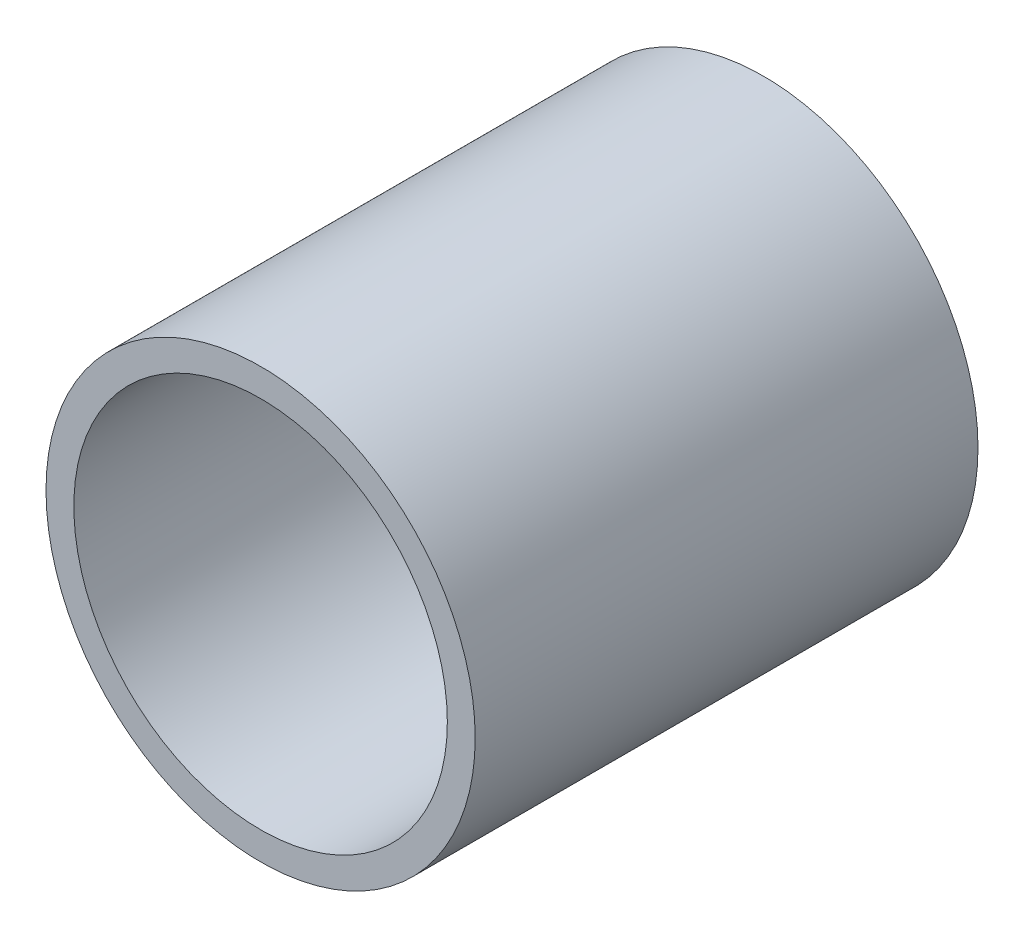
SolidWorks part; units mm, degrees
ref_plane "Front Plane" through (0, 0, 0) normal (0, 0, 1) x (1, 0, 0)
ref_plane "Top Plane" through (0, 0, 0) normal (0, 1, 0) x (1, 0, 0)
ref_plane "Right Plane" through (0, 0, 0) normal (1, 0, 0) x (0, 0, -1)
sketch "Sketch1" plane through (0, 0, 0) normal (0, 0, 1) x (1, 0, 0)
  circle A0 centre (0, 0) radius 6.6
  circle A1 centre (0, 0) radius 7.584
  dimension "D1" = 13.2
  dimension "D2" = 15.168
extrude "Boss-Extrude1" add sketch "Sketch1" along normal blind 17.77
